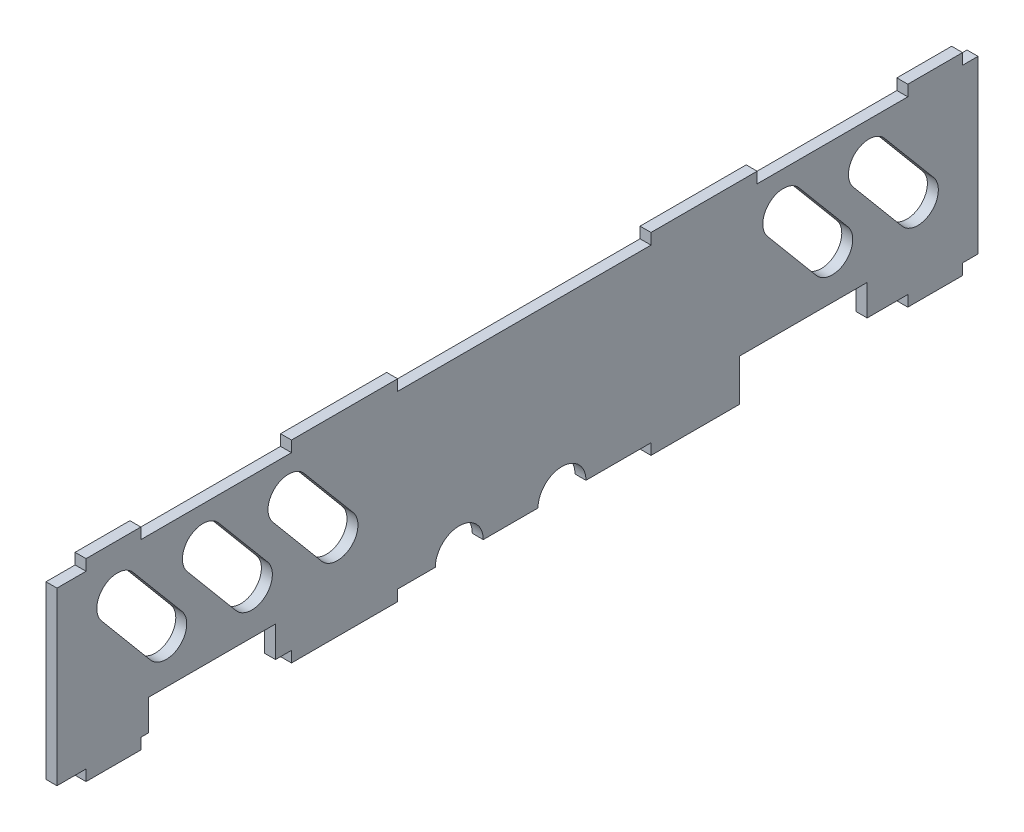
SolidWorks part; units mm, degrees
ref_plane "前视基准面" through (0, 0, 0) normal (0, 0, 1) x (1, 0, 0)
ref_plane "上视基准面" through (0, 0, 0) normal (0, 1, 0) x (1, 0, 0)
ref_plane "右视基准面" through (0, 0, 0) normal (1, 0, 0) x (0, 0, -1)
sketch "Sketch1" plane through (0, 0, 0) normal (1, 0, 0) x (0, 0, -1)
  line L0 (-1000, 0) -> (49000, 0) construction
  line L1 (0, 0) -> (0, -1.6)
  line L2 (0, -1.6) -> (-8, -1.6)
  line L3 (-8, -1.6) -> (-8, 0)
  line L4 (-8, 0) -> (0, 0)
  line L5 (-38, 0) -> (-30, 0)
  line L6 (-30, 0) -> (-30, -1.6)
  line L7 (-30, -1.6) -> (-38, -1.6)
  line L8 (-38, -1.6) -> (-38, 0)
  line L9 (-68, 0) -> (-60, 0) construction
  line L10 (-60, 0) -> (-60, -1.6) construction
  line L11 (-60, -1.6) -> (-68, -1.6) construction
  line L12 (-68, -1.6) -> (-68, 0) construction
  line L13 (-98, 0) -> (-90, 0)
  line L14 (-90, 0) -> (-90, -1.6)
  line L15 (-90, -1.6) -> (-98, -1.6)
  line L16 (-98, -1.6) -> (-98, 0)
  line L17 (-128, 0) -> (-120, 0)
  line L18 (-120, 0) -> (-120, -1.6)
  line L19 (-120, -1.6) -> (-128, -1.6)
  line L20 (-128, -1.6) -> (-128, 0)
  line L21 (-8, 0) -> (-38, 0) construction
  line L22 (-128, 0) -> (-132.25, 0)
  line L23 (-132.25, 0) -> (-132.25, 12.5)
  line L24 (-132.25, 12.5) -> (2.25, 12.5)
  line L25 (2.25, 12.5) -> (2.25, 0)
  line L26 (2.25, 0) -> (0, 0)
  line L27 (-132.25, 0) -> (-128, 0)
  line L28 (-120, 0) -> (-8, 0)
  line L29 (-90, -1.6) -> (-82.5, -1.6)
  line L30 (-82.5, -1.6) -> (-82.5, 0)
  line L31 (-90, 0) -> (-82.5, 0)
  line L32 (-38, -1.6) -> (-45.5, -1.6)
  line L33 (-45.5, -1.6) -> (-45.5, 0)
  line L34 (-45.5, 0) -> (-38, 0)
  dimension "D1" = 8
  dimension "D2" = 1.6
  dimension "D4" = 30
  dimension "D5" = 12.5
  dimension "D6" = 2.25
  dimension "D7" = 4.25
  dimension "D8" = 7.5
  dimension "D9" = 7.5
  dimension "D3" = 5
extrude "主结构" add sketch "Sketch1" along normal blind 1.6 contours L17 L28 L13 L9 L5 L4 L26 L25 L24 L23 L22 | L20 L19 L18 L17 | L16 L15 L14 L13 | L12 L11 L10 L9 | L8 L7 L6 L5 | L4 L3 L2 L1 | L29 L30 L28 L14 | L33 L32 L8 L28
mirror "Mirror1" about plane through (1.6, 12.5, 0) normal (0, 1, 0) of bodies 106
sketch "Sketch3" plane through (0, 0, 0) normal (1, 0, 0) x (0, 0, -1)
  line L1 (-120, 0) -> (-98, 0) construction
  line L2 (-117.9017, 4.5) -> (-101.3402, 4.5)
  line L3 (-101.3402, 4.5) -> (-101.3402, 0)
  line L5 (-31.5986, 0) -> (-31.5986, 4.5)
  line L6 (-30, 0) -> (-8, 0) construction
  line L7 (-31.5986, 4.5) -> (-14.9355, 4.5)
  line L8 (-14.9355, 4.5) -> (-14.9355, 0)
  line L10 (-31.5986, 0) -> (-31.5986, -1.6)
  line L11 (-77, 0) -> (-70, 0)
  line L12 (-62, 0) -> (-55, 0)
  line L13 (-30, -1.6) -> (-45.5, -1.6) construction
  line L14 (-31.5986, -1.6) -> (-14.9355, -1.6)
  line L15 (-14.9355, -1.6) -> (-14.9355, 0)
  line L16 (-82.5, 0) -> (-45.5, 0) construction
  line L17 (-117.9017, 0) -> (-117.9017, -1.6)
  line L18 (-117.9017, -1.6) -> (-101.3402, -1.6)
  line L25 (-117.9017, 4.5) -> (-117.9017, 0)
  line L26 (-101.3402, -1.6) -> (-101.3402, 0)
  line L29 (-117.9017, 4.5) -> (-118.9017, 4.5)
  line L30 (-118.9017, 4.5) -> (-118.9017, -1.6)
  line L31 (-118.9017, -1.6) -> (-117.9017, -1.6)
  line L32 (-101.3402, 4.5) -> (-100.3402, 4.5)
  line L33 (-100.3402, 4.5) -> (-100.3402, -1.6)
  line L34 (-100.3402, -1.6) -> (-101.3402, -1.6)
  line L35 (-31.5986, 4.5) -> (-32.5986, 4.5)
  line L36 (-32.5986, 4.5) -> (-32.5986, -1.6)
  line L37 (-32.5986, -1.6) -> (-31.5986, -1.6)
  line L38 (-14.9355, 4.5) -> (-13.9355, 4.5)
  line L39 (-13.9355, 4.5) -> (-13.9355, -1.6)
  line L40 (-13.9355, -1.6) -> (-14.9355, -1.6)
  arc A0 (-77, 0) -> (-70, 0) centre (-73.5, 0) cw
  arc A1 (-62, 0) -> (-55, 0) centre (-58.5, 0) cw
  point P28 (0, 0)
  point P34 (-117.9017, 2.25)
  dimension "D1" = 3.5
  dimension "D2" = 73.5
  dimension "D3" = 58.5
  dimension "D4" = 4.5
  dimension "D5" = 31.5986
  dimension "D6" = 14.9355
  dimension "D7" = 101.3402
  dimension "D8" = 16.5615
  dimension "D9" = 1
extrude "天线槽和侧板连接件让位" cut sketch "Sketch3" along normal through all
sketch "Sketch4" plane through (0, 0, 0) normal (1, 0, 0) x (0, 0, -1)
  line L0 (-13.6741, 19.5) -> (-6.5417, 11) construction
  line L1 (-11.376, 21.4284) -> (-4.2436, 12.9284)
  line L2 (-15.9722, 17.5716) -> (-8.8399, 9.0716)
  line L3 (-123.4293, 19.5) -> (-116.297, 11) construction
  line L4 (-121.1312, 21.4284) -> (-113.9989, 12.9284)
  line L5 (-125.7275, 17.5716) -> (-118.5951, 9.0716)
  line L6 (-26.1741, 19.5) -> (-19.0417, 11) construction
  line L7 (-23.876, 21.4284) -> (-16.7436, 12.9284)
  line L8 (-28.4722, 17.5716) -> (-21.3399, 9.0716)
  line L9 (-13.6741, 19.5) -> (-26.1741, 19.5) construction
  line L10 (-110.9293, 19.5) -> (-103.797, 11) construction
  line L11 (-108.6312, 21.4284) -> (-101.4989, 12.9284)
  line L12 (-113.2275, 17.5716) -> (-106.0951, 9.0716)
  line L13 (-98.4293, 19.5) -> (-91.297, 11) construction
  line L14 (-96.1312, 21.4284) -> (-88.9989, 12.9284)
  line L15 (-100.7275, 17.5716) -> (-93.5951, 9.0716)
  line L16 (-123.4293, 19.5) -> (-110.9293, 19.5) construction
  line L17 (-30, 25) -> (-8, 25) construction
  line L18 (-32.5986, 4.5) -> (-13.9355, 4.5) construction
  arc A0 (-11.376, 21.4284) -> (-15.9722, 17.5716) centre (-13.6741, 19.5) ccw
  arc A1 (-8.8399, 9.0716) -> (-4.2436, 12.9284) centre (-6.5417, 11) ccw
  arc A2 (-121.1312, 21.4284) -> (-125.7275, 17.5716) centre (-123.4293, 19.5) ccw
  arc A3 (-118.5951, 9.0716) -> (-113.9989, 12.9284) centre (-116.297, 11) ccw
  arc A4 (-23.876, 21.4284) -> (-28.4722, 17.5716) centre (-26.1741, 19.5) ccw
  arc A5 (-21.3399, 9.0716) -> (-16.7436, 12.9284) centre (-19.0417, 11) ccw
  arc A6 (-108.6312, 21.4284) -> (-113.2275, 17.5716) centre (-110.9293, 19.5) ccw
  arc A7 (-106.0951, 9.0716) -> (-101.4989, 12.9284) centre (-103.797, 11) ccw
  arc A8 (-96.1312, 21.4284) -> (-100.7275, 17.5716) centre (-98.4293, 19.5) ccw
  arc A9 (-93.5951, 9.0716) -> (-88.9989, 12.9284) centre (-91.297, 11) ccw
  point P2 (-10.1079, 15.25)
  point P7 (-119.8632, 15.25)
  point P17 (-22.6079, 15.25)
  point P24 (-107.3632, 15.25)
  point P31 (-94.8632, 15.25)
  dimension "D1" = 3
  dimension "D2" = 12.5
  dimension "D3" = 12.5
  dimension "D4" = 5.5
  dimension "D6" = 8.5
  dimension "D7" = 50
  dimension "D5" = 2
extrude "风道" cut sketch "Sketch4" along normal blind 1.6
